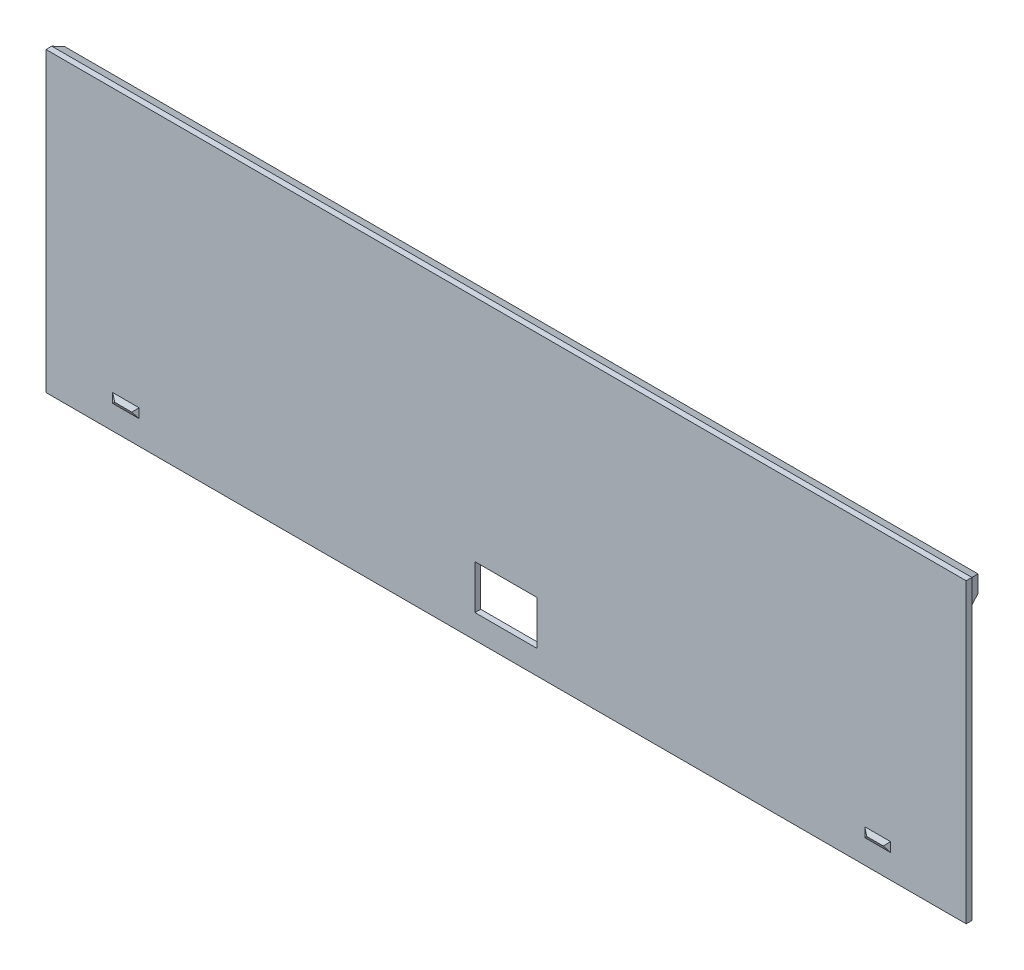
SolidWorks part; units mm, degrees
ref_plane "前视基准面" through (0, 0, 0) normal (0, 0, 1) x (1, 0, 0)
ref_plane "上视基准面" through (0, 0, 0) normal (0, 1, 0) x (1, 0, 0)
ref_plane "右视基准面" through (0, 0, 0) normal (1, 0, 0) x (0, 0, -1)
other "Configuration Table"
sketch "草图1" plane through (0, 0, 0) normal (0, 0, 1) x (1, 0, 0)
  line L0 (-96, 26) -> (96, 26) construction
  line L1 (-96, -31) -> (96, -31)
  line L2 (-96, -31) -> (-96, 31)
  line L3 (-96, 31) -> (96, 31)
  line L4 (96, -31) -> (96, 31)
  line L5 (-96, -31) -> (96, 31) construction
  line L6 (-96, 31) -> (96, -31) construction
  point P0 (0, 0)
  dimension "D1" = 192
  dimension "D2" = 62
  dimension "D3" = 57
extrude "凸台-拉伸1" add sketch "草图1" along normal blind 1.2
sketch "草图2" plane through (0, 0, 0) normal (0, 0, 1) x (1, 0, 0)
  line L0 (-96, 26) -> (96, 26) construction
  line L1 (-96, 31) -> (-96, -31) construction
  line L2 (96, -31) -> (96, 31) construction
  line L3 (-96, -31) -> (96, -31) construction
  line L4 (-96, 26) -> (96, 26)
  line L5 (96, 26) -> (96, 31)
  line L6 (96, 31) -> (-96, 31)
  line L7 (-96, 31) -> (-96, 26)
  dimension "D1" = 57
extrude "凸台-拉伸2" add sketch "草图2" against normal blind 2 draft 20
sketch "草图3" plane through (0, 0, 1.2) normal (0, 0, 1) x (1, 0, 0)
  line L0 (-96, -26) -> (96, -26) construction
  line L2 (-96, 31) -> (-96, -31) construction
  line L3 (96, -31) -> (96, 31) construction
  line L4 (-96, -31) -> (96, -31) construction
  line L5 (-96, -21.4) -> (96, -21.4) construction
  line L7 (-6.5, -16.8) -> (6.5, -16.8)
  line L8 (-6.5, -16.8) -> (-6.5, -26)
  line L9 (-6.5, -26) -> (6.5, -26)
  line L10 (6.5, -16.8) -> (6.5, -26)
  line L11 (-6.5, -16.8) -> (6.5, -26) construction
  line L12 (-6.5, -26) -> (6.5, -16.8) construction
  point P11 (0, -21.4)
  dimension "D1" = 5
  dimension "D2" = 4.6
  dimension "D3" = 13
extrude "切除-拉伸1" cut sketch "草图3" against normal blind 2
sketch "草图4" plane through (0, 0, 1.2) normal (0, 0, 1) x (1, 0, 0)
  line L0 (-96, -26) -> (96, -26) construction
  line L1 (-96, 31) -> (-96, -31) construction
  line L2 (96, -31) -> (96, 31) construction
  line L3 (-96, -31) -> (96, -31) construction
  line L5 (-82.0836, -26) -> (-76.5547, -26)
  line L6 (-82.0836, -26) -> (-82.0836, -24.0297)
  line L7 (-82.0836, -24.0297) -> (-76.5547, -24.0297)
  line L8 (-76.5547, -26) -> (-76.5547, -24.0297)
  line L9 (74.8534, -26) -> (80.2406, -26)
  line L10 (74.8534, -26) -> (74.8534, -24.0297)
  line L11 (74.8534, -24.0297) -> (80.2406, -24.0297)
  line L12 (80.2406, -26) -> (80.2406, -24.0297)
  dimension "D1" = 5
extrude "凸台-拉伸3" add sketch "草图4" along normal blind 2 draft 60
